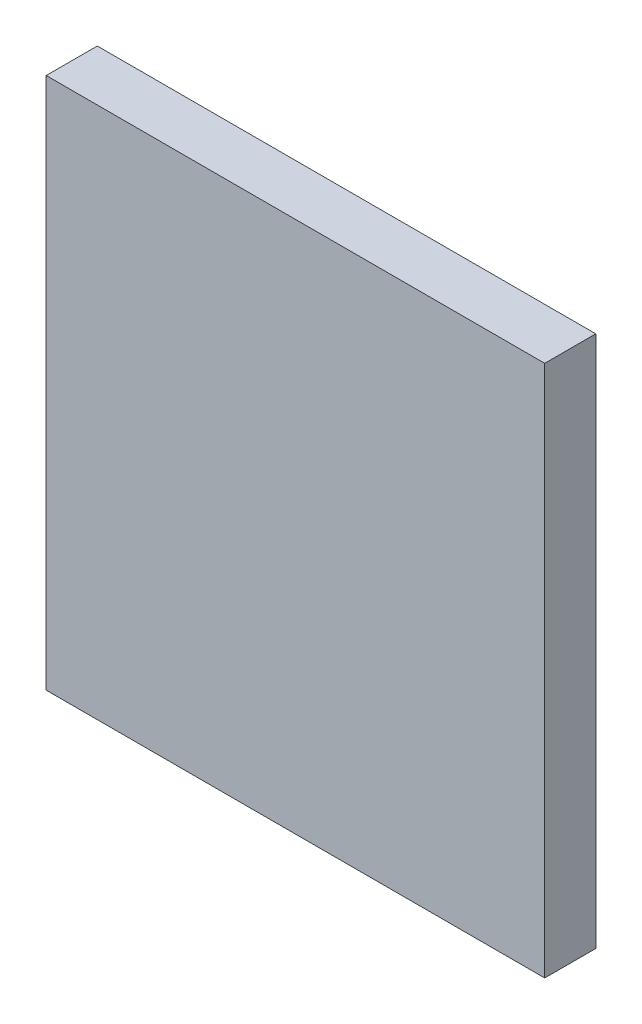
SolidWorks part; units mm, degrees
ref_plane "Front Plane" through (0, 0, 0) normal (0, 0, 1) x (1, 0, 0)
ref_plane "Top Plane" through (0, 0, 0) normal (0, 1, 0) x (1, 0, 0)
ref_plane "Right Plane" through (0, 0, 0) normal (1, 0, 0) x (0, 0, -1)
sketch "Sketch1" plane through (0, 0, 0) normal (0, 0, 1) x (1, 0, 0)
  line L0 (104.0973, 51.3118) -> (91.5862, 51.3118)
  line L1 (104.0973, 51.3118) -> (169.2083, 51.3118)
  line L2 (104.0973, 51.3118) -> (104.0973, -52.9195)
  line L3 (104.0973, -52.9195) -> (169.2083, -52.9195)
  line L4 (169.2083, 51.3118) -> (169.2083, -52.9195)
  line L5 (91.5862, 51.3118) -> (91.5862, -52.9195)
  line L6 (91.5862, -52.9195) -> (104.0973, -52.9195)
  line L7 (169.2083, 51.3118) -> (178.6647, 51.3118)
  line L8 (178.6647, 51.3118) -> (178.6647, -52.9195)
  line L9 (178.6647, -52.9195) -> (169.2083, -52.9195)
  line L10 (178.6647, 51.3118) -> (189.1907, 51.3118)
  line L11 (189.1907, 51.3118) -> (189.1907, -52.9195)
  line L12 (189.1907, -52.9195) -> (178.6647, -52.9195)
extrude "Boss-Extrude1" add sketch "Sketch1" along normal blind 10 contours L4 L1 L2 L3 | L5 L6 L2 L0 | L12 L11 L10 L8 | L9 L8 L7 L4
